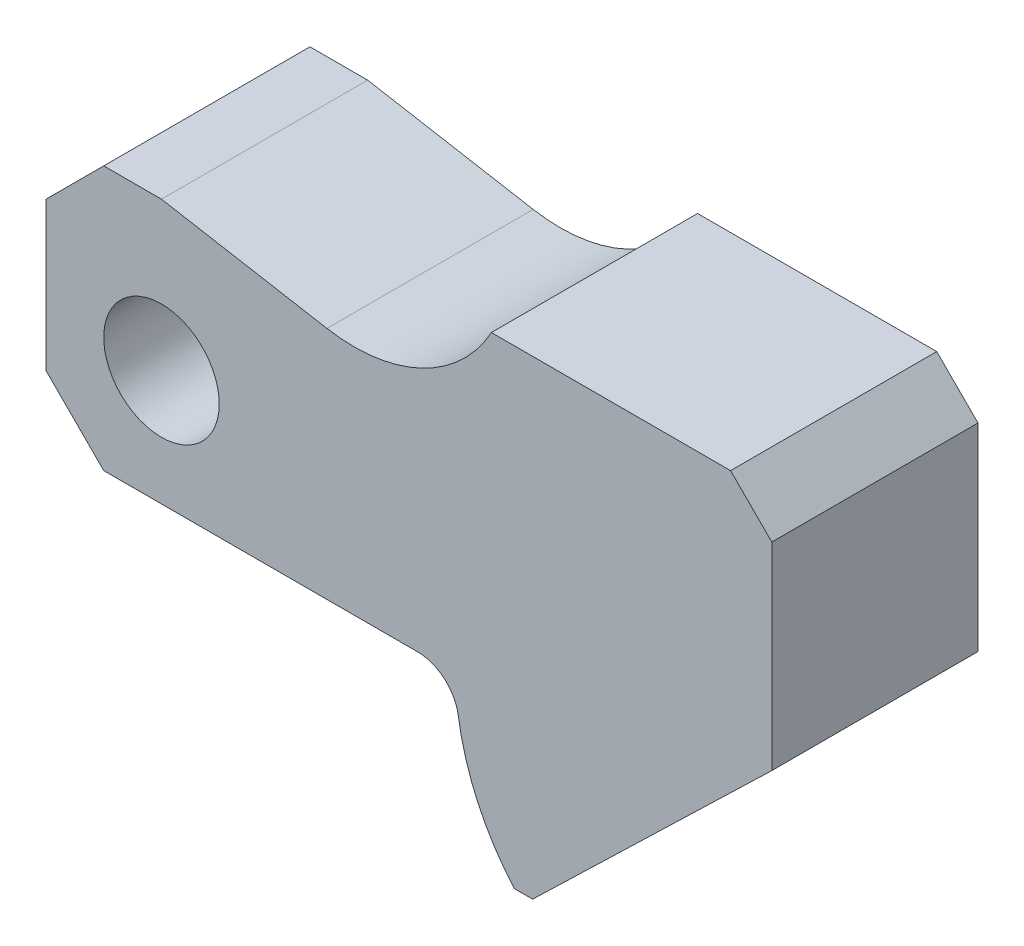
SolidWorks part; units mm, degrees
material "Brass"
ref_plane "Front Plane" through (0, 0, 0) normal (0, 0, 1) x (1, 0, 0)
ref_plane "Top Plane" through (0, 0, 0) normal (0, 1, 0) x (1, 0, 0)
ref_plane "Right Plane" through (0, 0, 0) normal (1, 0, 0) x (0, 0, -1)
sketch "Sketch1" plane through (0, 0, 0) normal (0, 0, 1) x (1, 0, 0)
  line L0 (0, 0) -> (-76.0965, 0)
  line L1 (-76.0965, 0) -> (-90.0965, 14)
  line L2 (-90.0965, 14) -> (-90.0965, 50)
  line L3 (-90.0965, 50) -> (-76.0965, 64)
  line L4 (-76.0965, 64) -> (-62.0965, 64)
  line L5 (-62.0965, 64) -> (-21.9721, 56.925)
  line L6 (17.9035, 76) -> (75.9035, 76)
  line L7 (75.9035, 76) -> (85.9035, 66)
  line L8 (85.9035, 66) -> (85.9035, 18)
  line L9 (85.9035, 18) -> (27.9035, -38)
  line L10 (27.9035, -38) -> (23.4429, -38)
  circle A0 centre (-62.0965, 28) radius 14
  arc A1 (17.9035, 76) -> (-21.9721, 56.925) centre (-15.3735, 94.3477) cw
  arc A2 (9.8913, -8.5294) -> (0, 0) centre (0, -10) ccw
  arc A3 (23.4429, -38) -> (9.8913, -8.5294) centre (67.2607, 0) cw
  dimension "D9" = 28
  dimension "D11" = 38
  dimension "D13" = 58
  dimension "D14" = 10
  dimension "D1" = 28
  dimension "D2" = 45
  dimension "D3" = 14
  dimension "D4" = 28
  dimension "D5" = 64
  dimension "D6" = 14
  dimension "D7" = 28
  dimension "D8" = 45
  dimension "D10" = 10
  dimension "D12" = 38
  dimension "D15" = 38
  dimension "D16" = 58
  dimension "D17" = 48
  dimension "D18" = 10
  dimension "D19" = 114
  dimension "D20" = 45
  dimension "D21" = 58
  dimension "D22" = 176
extrude "Boss-Extrude1" add sketch "Sketch1" along normal blind 50
